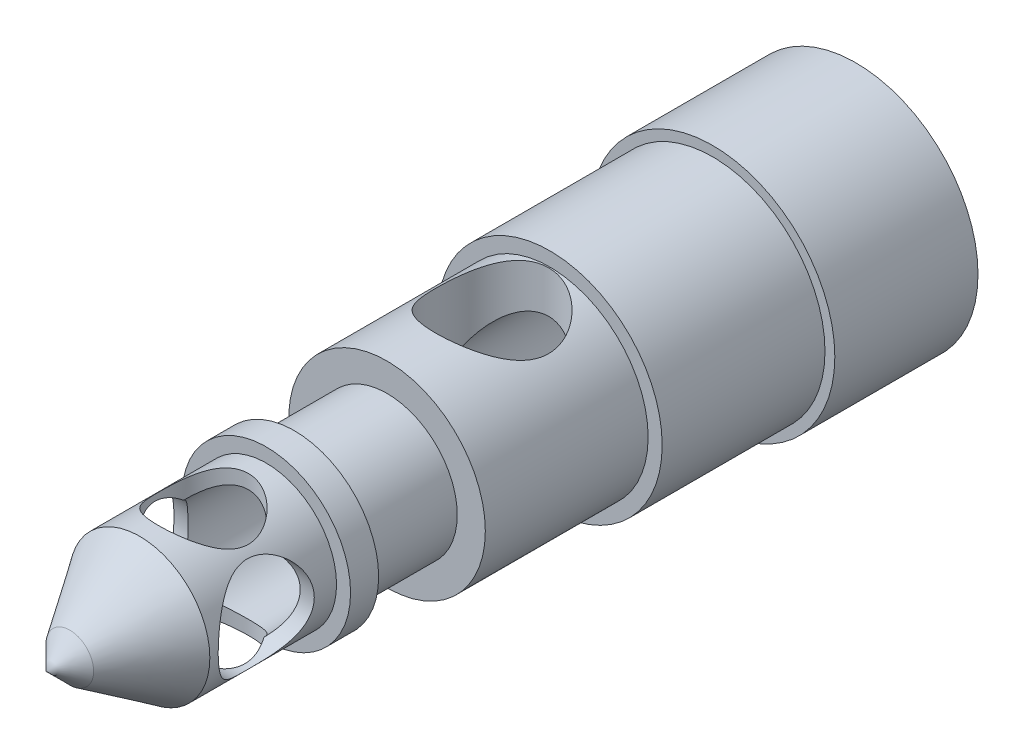
SolidWorks part; units mm, degrees
ref_plane "Plan de face" through (0, 0, 0) normal (0, 0, 1) x (1, 0, 0)
ref_plane "Plan de dessus" through (0, 0, 0) normal (0, 1, 0) x (1, 0, 0)
ref_plane "Plan de droite" through (0, 0, 0) normal (1, 0, 0) x (0, 0, -1)
sketch "Esquisse1" plane through (0, 0, 0) normal (0, 0, 1) x (1, 0, 0)
  circle A0 centre (0, 0) radius 2.175
extrude "Boss.-Extru.1" add sketch "Esquisse1" along normal blind 2.55
sketch "Esquisse2" plane through (0, 0, 2.55) normal (0, 0, 1) x (1, 0, 0)
  circle A0 centre (0, 0) radius 2
extrude "Boss.-Extru.2" add sketch "Esquisse2" along normal blind 2.9
sketch "Esquisse3" plane through (0, 0, 5.45) normal (0, 0, 1) x (1, 0, 0)
  circle A0 centre (0, 0) radius 1.75
extrude "Boss.-Extru.3" add sketch "Esquisse3" along normal blind 2.9
sketch "Esquisse4" plane through (0, 0, 8.35) normal (0, 0, 1) x (1, 0, 0)
  circle A0 centre (0, 0) radius 1.25
extrude "Boss.-Extru.4" add sketch "Esquisse4" along normal blind 1.65
sketch "Esquisse6" plane through (0, 0, 10) normal (0, 0, 1) x (1, 0, 0)
  circle A0 centre (0, 0) radius 1.5
extrude "Boss.-Extru.5" add sketch "Esquisse6" along normal blind 0.5
sketch "Esquisse7" plane through (0, 0, 10.5) normal (0, 0, 1) x (1, 0, 0)
  circle A0 centre (0, 0) radius 1.25
extrude "Boss.-Extru.6" add sketch "Esquisse7" along normal blind 1
sketch "Esquisse8" plane through (0, 0, 0) normal (1, 0, 0) x (0, 0, -1)
  line L0 (-14.4248, 0) -> (0, 0) construction
  line L1 (-11.5, 1.25) -> (-11.5, 0)
  line L2 (-11.5, 1.25) -> (-11.5, -1.25) construction
  line L3 (-11.5, 0) -> (-14.4248, 0)
  line L4 (-14.4248, 0) -> (-14.0004, 0.4244)
  line L5 (-14.0004, 0.4244) -> (-13.4734, 0.7742)
  line L6 (-13.4734, 0.7742) -> (-12.7565, 1.25)
  line L7 (-12.7565, 1.25) -> (-11.5, 1.25)
revolve "Révolution1" add sketch "Esquisse8" angle 360 about L0
sketch "Esquisse9" plane through (0, 0, 0) normal (0, 1, 0) x (1, 0, 0)
  circle A0 centre (0, -6.4799) radius 1.0074
  point P2 (0, -6.5613)
  point P3 (0, -6.4799)
extrude "Enlèv. mat.-Extru.1" cut sketch "Esquisse9" against normal through all both and the other way through all
sketch "Esquisse10" plane through (0, 0, 0) normal (0, 1, 0) x (1, 0, 0)
  circle A0 centre (0, -11.6213) radius 0.8024
  point P2 (0, -11.6213)
extrude "Enlèv. mat.-Extru.3" cut sketch "Esquisse10" against normal through all both and the other way through all
sketch "Esquisse11" plane through (0, 0, 0) normal (1, 0, 0) x (0, 0, -1)
  circle A0 centre (-11.752, 0) radius 0.8554
extrude "Enlèv. mat.-Extru.4" cut sketch "Esquisse11" against normal through all both and the other way through all
sketch "Esquisse12" plane through (0, 0, 0) normal (0, 0, -1) x (-1, 0, 0)
  circle A0 centre (0, 0) radius 1
  point P3 (18.5938, 19.1823)
extrude "Enlèv. mat.-Extru.5" cut sketch "Esquisse12" against normal blind 12.5
